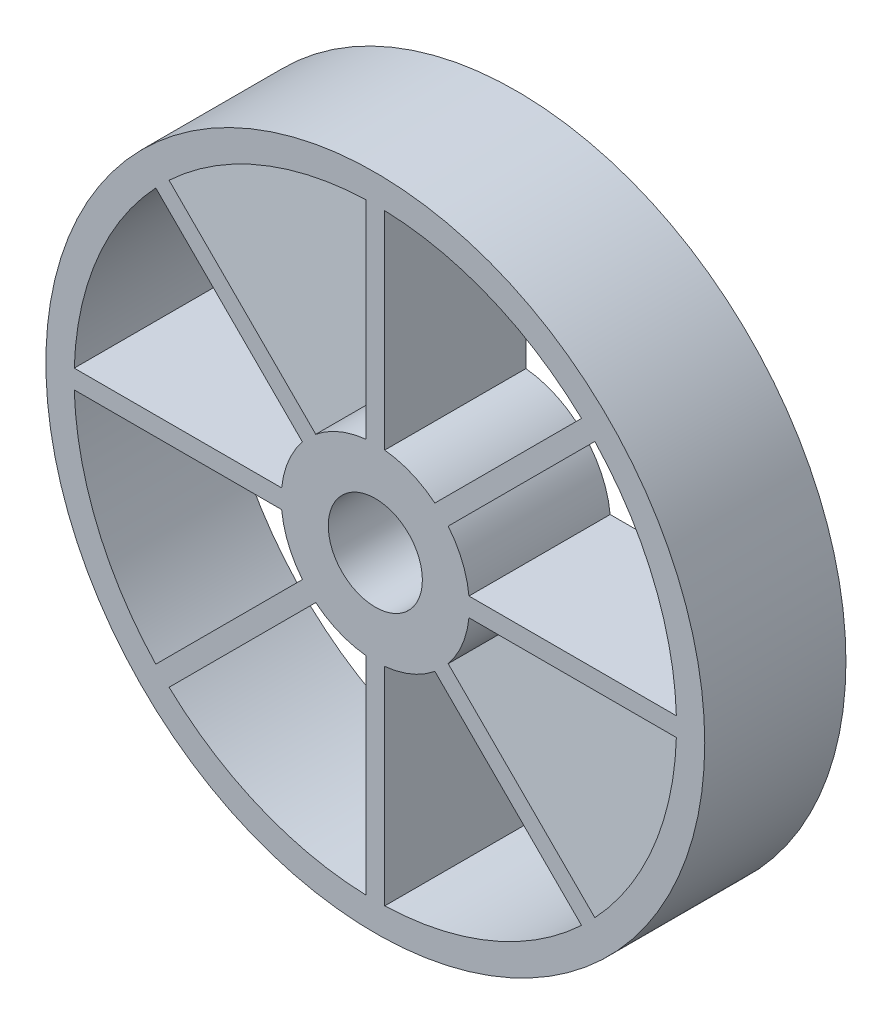
SolidWorks part; units mm, degrees
ref_plane "Ön Düzlem" through (0, 0, 0) normal (0, 0, 1) x (1, 0, 0)
ref_plane "Üst Düzlem" through (0, 0, 0) normal (0, 1, 0) x (1, 0, 0)
ref_plane "Sağ Düzlem" through (0, 0, 0) normal (1, 0, 0) x (0, 0, -1)
sketch "Sketch1" plane through (0, 0, 0) normal (0, 0, 1) x (1, 0, 0)
  circle A0 centre (0, 0) radius 5000
  circle A1 centre (0, 0) radius 10000
extrude "Boss-Extrude1" add sketch "Sketch1" along normal blind 15000
sketch "Sketch2" plane through (0, 0, 15000) normal (0, 0, 1) x (1, 0, 0)
  circle A0 centre (0, 0) radius 32000
  circle A1 centre (0, 0) radius 35000
extrude "Boss-Extrude5" add sketch "Sketch2" against normal blind 15000 separate body contours A1 A0
sketch "Sketch3" plane through (0, 0, 0) normal (0, 0, 1) x (1, 0, 0)
  line L2 (6328.5169, 7742.7304) -> (21909.259, 23323.4725)
  line L3 (-1000, 9949.8744) -> (-1000, 31984.3712)
  line L4 (1000, 9949.8744) -> (1000, 31984.3712)
  line L5 (7742.7304, 6328.5169) -> (23323.4725, 21909.259)
  line L6 (9949.8744, 1000) -> (31984.3712, 1000)
  line L7 (9949.8744, -1000) -> (31984.3712, -1000)
  line L8 (7742.7304, -6328.5169) -> (23323.4725, -21909.259)
  line L9 (6328.5169, -7742.7304) -> (21909.259, -23323.4725)
  line L10 (1000, -9949.8744) -> (1000, -31984.3712)
  line L11 (-1000, -9949.8744) -> (-1000, -31984.3712)
  line L12 (-6328.5169, -7742.7304) -> (-21909.259, -23323.4725)
  line L13 (-7742.7304, -6328.5169) -> (-23323.4725, -21909.259)
  line L14 (-9949.8744, -1000) -> (-31984.3712, -1000)
  line L15 (-9949.8744, 1000) -> (-31984.3712, 1000)
  line L16 (-7742.7304, 6328.5169) -> (-23323.4725, 21909.259)
  line L17 (-6328.5169, 7742.7304) -> (-21909.259, 23323.4725)
  arc A1 (1000, 31984.3712) -> (-1000, 31984.3712) centre (0, 0) ccw
  arc A2 (1000, 9949.8744) -> (-1000, 9949.8744) centre (0, 0) ccw
  arc A3 (7742.7304, 6328.5169) -> (6328.5169, 7742.7304) centre (0, 0) ccw
  arc A4 (23323.4725, 21909.259) -> (21909.259, 23323.4725) centre (0, 0) ccw
  arc A5 (9949.8744, -1000) -> (9949.8744, 1000) centre (0, 0) ccw
  arc A6 (31984.3712, -1000) -> (31984.3712, 1000) centre (0, 0) ccw
  arc A7 (6328.5169, -7742.7304) -> (7742.7304, -6328.5169) centre (0, 0) ccw
  arc A8 (21909.259, -23323.4725) -> (23323.4725, -21909.259) centre (0, 0) ccw
  arc A9 (-1000, -9949.8744) -> (1000, -9949.8744) centre (0, 0) ccw
  arc A10 (-1000, -31984.3712) -> (1000, -31984.3712) centre (0, 0) ccw
  arc A11 (-7742.7304, -6328.5169) -> (-6328.5169, -7742.7304) centre (0, 0) ccw
  arc A12 (-23323.4725, -21909.259) -> (-21909.259, -23323.4725) centre (0, 0) ccw
  arc A13 (-9949.8744, 1000) -> (-9949.8744, -1000) centre (0, 0) ccw
  arc A14 (-31984.3712, 1000) -> (-31984.3712, -1000) centre (0, 0) ccw
  arc A15 (-6328.5169, 7742.7304) -> (-7742.7304, 6328.5169) centre (0, 0) ccw
  arc A16 (-21909.259, 23323.4725) -> (-23323.4725, 21909.259) centre (0, 0) ccw
  point P37 (0, 0)
  dimension "D1" = 8
extrude "Boss-Extrude6" add sketch "Sketch3" along normal blind 15000 contours A2 L3 A1 L4 | L16 A16 L17 A15 | L14 A14 L15 A13 | L10 A10 L11 A9 | L6 A6 L7 A5 | L8 A8 L9 A7 | L2 A4 L5 A3 | L12 A12 L13 A11
